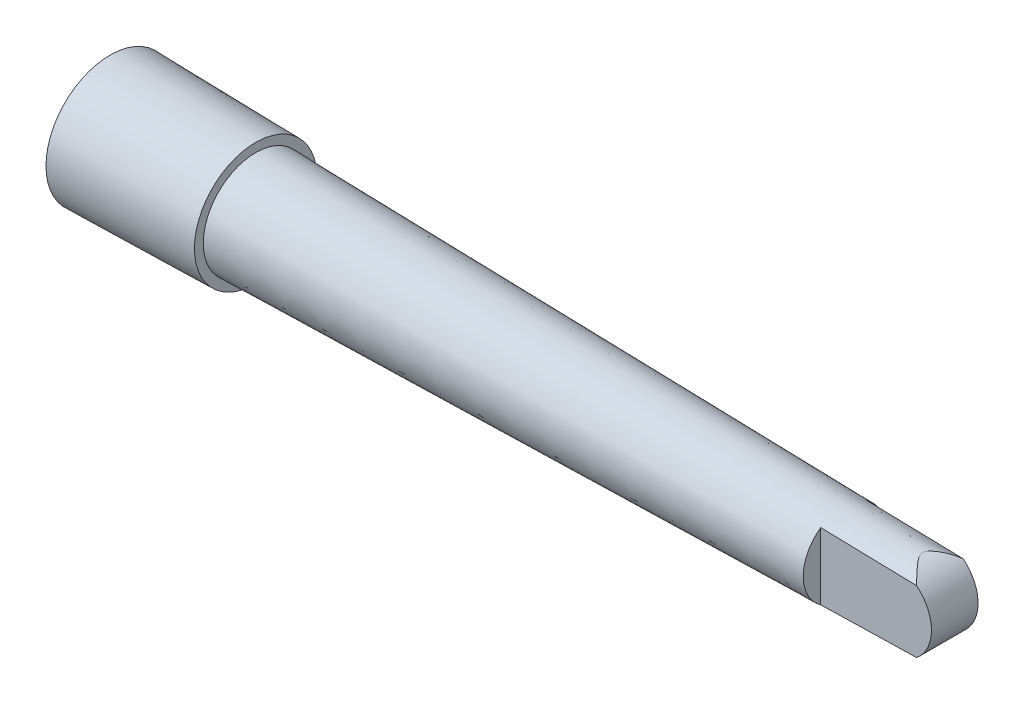
SolidWorks part; units mm, degrees
ref_plane "Front Plane" through (0, 0, 0) normal (0, 0, 1) x (1, 0, 0)
ref_plane "Top Plane" through (0, 0, 0) normal (0, 1, 0) x (1, 0, 0)
ref_plane "Right Plane" through (0, 0, 0) normal (1, 0, 0) x (0, 0, -1)
sketch "Sketch1" plane through (0, 0, 0) normal (0, 0, 1) x (1, 0, 0)
  line L6 (0, 0) -> (31.5, 0)
  line L7 (0, 0) -> (0, 2.75)
  line L8 (0, 2.75) -> (6.25, 2.63)
  line L9 (6.25, 2.63) -> (6.25, 2.25)
  line L10 (6.25, 2.25) -> (31.5, 1.75)
  line L11 (31.5, 1.75) -> (31.5, 0)
  dimension "D1" = 2.75
  dimension "D2" = 2.63
  dimension "D3" = 2.25
  dimension "D4" = 1.75
  dimension "D5" = 31.5
  dimension "D6" = 6.25
revolve "Revolve2" add sketch "Sketch1" angle 360 about L6
sketch "Sketch3" plane through (0, 0, 0) normal (0, 0, 1) x (1, 0, 0)
  line L0 (31.5, 0) -> (36.2528, 0) construction
  line L1 (31.5, -1.75) -> (31.5, 1.75) construction
  line L2 (31.5, 1.75) -> (34.86, 1.6835)
  line L3 (31.5, -1.75) -> (34.86, -1.6835)
  line L4 (31.5, 1.75) -> (6.25, 2.25) construction
  line L5 (6.25, -2.25) -> (31.5, -1.75) construction
  line L6 (31.5, 1.75) -> (31.5, -1.75)
  arc A0 (34.86, 1.6835) -> (34.86, -1.6835) centre (34.5389, 0) cw
  dimension "D1" = 3.36
extrude "Boss-Extrude3" add sketch "Sketch3" along normal mid plane 2
sketch "Sketch9" plane through (0, 0, 0) normal (0, 0, 1) x (1, 0, 0)
  line L0 (31.5, 1.75) -> (31.5, 2.5)
  line L1 (31.5, 2.5) -> (37.1303, 2.5)
  line L2 (37.1303, 2.5) -> (37.1303, 1.6385)
  line L3 (37.1303, 1.6385) -> (31.5, 1.75)
  line L4 (34.86, 1.6835) -> (31.5, 1.75) construction
  line L5 (31.5, 0) -> (37.7143, 0) construction
  line L6 (31.5, -1.4361) -> (31.5, 1.4361) construction
  dimension "D1" = 2.5
revolve "Cut-Revolve9" cut sketch "Sketch9" angle 360 about L5
sketch "Sketch7" plane through (0, 0, 0) normal (0, 0, 1) x (1, 0, 0)
  line L0 (31.5, 1.75) -> (31.5, 2.5888)
  line L1 (31.5, 2.5888) -> (36.8253, 2.5888)
  line L2 (36.8253, 2.5888) -> (36.8253, 1.6445)
  line L3 (36.8253, 1.6445) -> (31.5, 1.75)
  line L4 (34.86, 1.6835) -> (31.5, 1.75) construction
  line L5 (31.5, 0) -> (36.9389, 0) construction
  line L6 (31.5, 1.4361) -> (31.5, -1.4361) construction
revolve "Cut-Revolve8" cut sketch "Sketch7" angle 360 about L5
